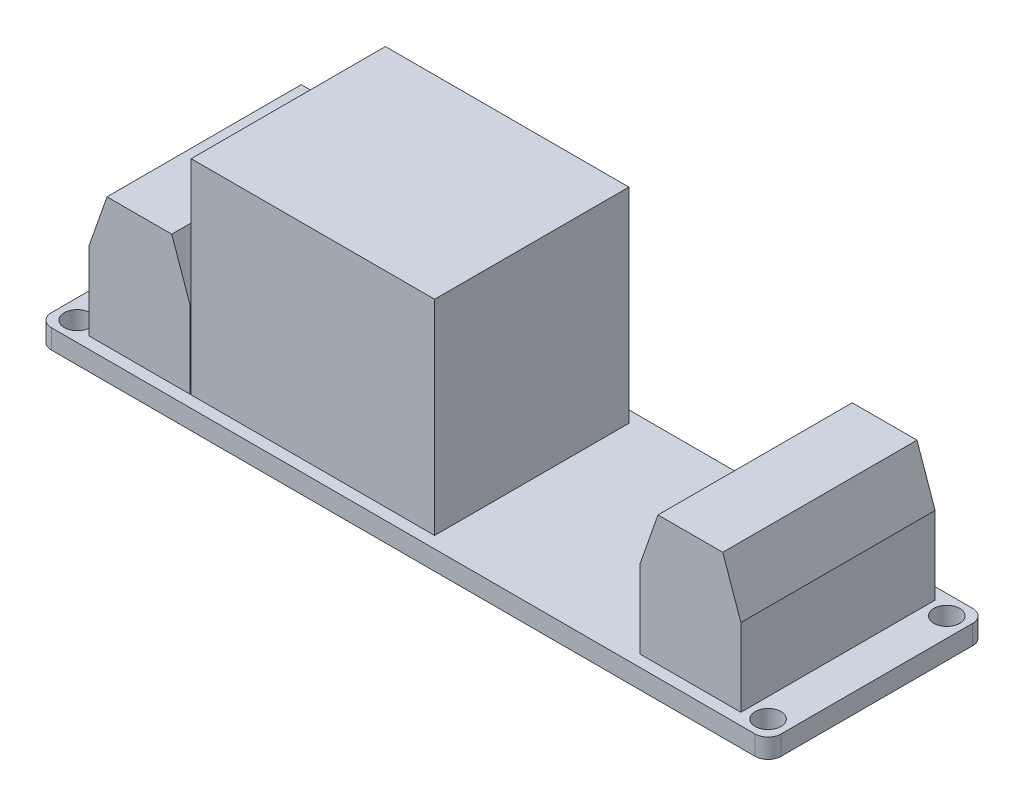
SolidWorks part; units mm, degrees
ref_plane "Front Plane" through (0, 0, 0) normal (0, 0, 1) x (1, 0, 0)
ref_plane "Top Plane" through (0, 0, 0) normal (0, 1, 0) x (1, 0, 0)
ref_plane "Right Plane" through (0, 0, 0) normal (1, 0, 0) x (0, 0, -1)
sketch "Sketch1" plane through (0, 0, 0) normal (0, 1, 0) x (1, 0, 0)
  line L1 (-28.175, 8.4) -> (28.175, 8.4)
  line L2 (-28.175, 8.4) -> (-28.175, -8.4)
  line L3 (-28.175, -8.4) -> (28.175, -8.4)
  line L4 (28.175, 8.4) -> (28.175, -8.4)
  line L5 (-28.175, 8.4) -> (28.175, -8.4) construction
  line L6 (-28.175, -8.4) -> (28.175, 8.4) construction
  point P0 (0, 0)
  dimension "D1" = 56.35
  dimension "D2" = 16.8
extrude "Boss-Extrude1" add sketch "Sketch1" along normal blind 1.5
sketch "Sketch2" plane through (0, 1.5, 0) normal (0, 1, 0) x (1, 0, 0)
  line L0 (-28.175, 8.4) -> (-28.175, -8.4) construction
  line L1 (28.175, 8.4) -> (-28.175, 8.4) construction
  circle A0 centre (-26.675, 6.9) radius 1
  dimension "D1" = 2
  dimension "D2" = 1.5
  dimension "D3" = 1.5
extrude "Cut-Extrude1" cut sketch "Sketch2" against normal through all
mirror "Mirror1" about plane through (0, 0, 0) normal (0, 0, 1) of "Cut-Extrude1"
mirror "Mirror2" about plane through (0, 0, 0) normal (1, 0, 0) of "Mirror1", "Cut-Extrude1"
fillet "Fillet1" radius 1 4 edges at (28.175, 0.75, 8.4) (28.175, 0.75, -8.4) (-28.175, 0.75, -8.4) (-28.175, 0.75, 8.4)
sketch "Sketch3" plane through (0, 0, 0) normal (0, 0, 1) x (1, 0, 0)
  line L0 (18.775, 11.5) -> (17.375, 7.5)
  line L1 (25.175, 1.5) -> (17.375, 1.5)
  line L2 (25.175, 1.5) -> (25.175, 7.5)
  line L3 (23.775, 11.5) -> (18.775, 11.5)
  line L4 (17.375, 1.5) -> (17.375, 7.5)
  line L5 (23.775, 11.5) -> (25.175, 7.5)
  line L6 (-27.175, 1.5) -> (27.175, 1.5) construction
  point P8 (21.275, 11.5)
  point P9 (21.275, 1.5)
  dimension "D1" = 10
  dimension "D2" = 7.8
  dimension "D3" = 4
  dimension "D4" = 5
  dimension "D5" = 3
extrude "Boss-Extrude2" add sketch "Sketch3" along normal mid plane 15
mirror "Mirror3" about plane through (0, 0, 0) normal (1, 0, 0) of "Boss-Extrude2"
sketch "Sketch4" plane through (0, 0, 0) normal (0, 0, 1) x (1, 0, 0)
  line L1 (-17.275, 1.5) -> (1.525, 1.5)
  line L2 (-17.275, 1.5) -> (-17.275, 17.3)
  line L3 (-17.275, 17.3) -> (1.525, 17.3)
  line L4 (1.525, 1.5) -> (1.525, 17.3)
  line L5 (-27.175, 1.5) -> (27.175, 1.5) construction
  line L6 (-17.375, 7.5) -> (-17.375, 1.5) construction
  dimension "D1" = 18.8
  dimension "D2" = 15.8
  dimension "D3" = 0.1
extrude "Boss-Extrude3" add sketch "Sketch4" along normal mid plane 15
